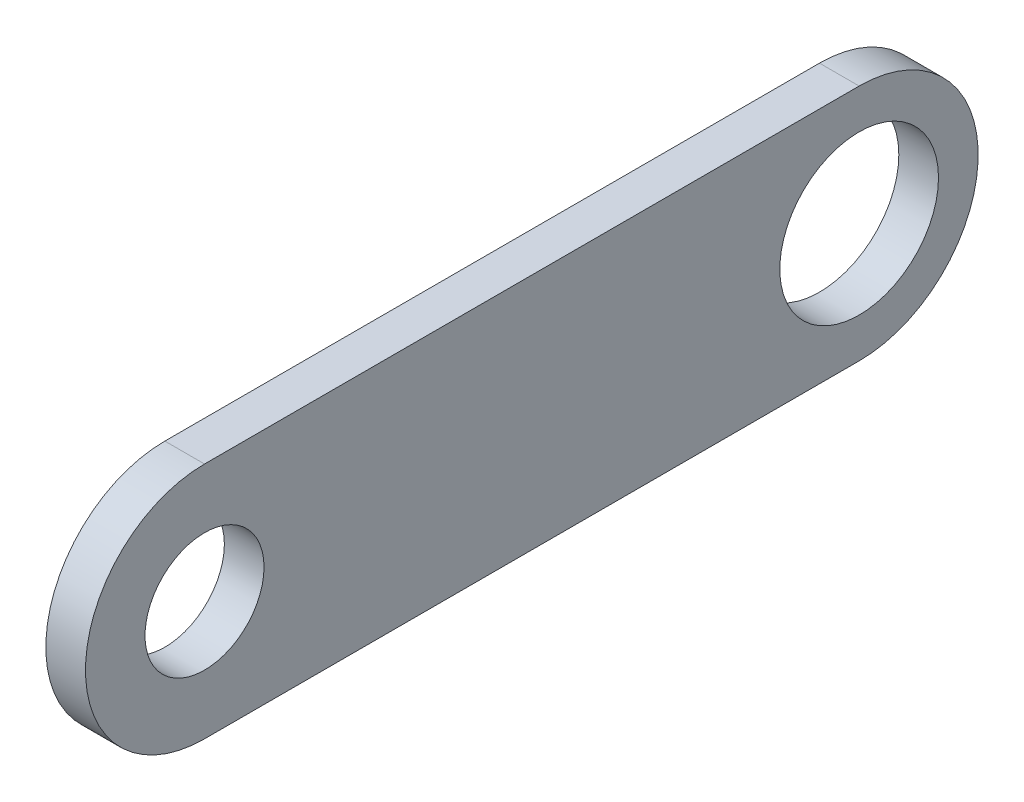
SolidWorks part; units mm, degrees
ref_plane "正面" through (0, 0, 0) normal (0, 0, 1) x (1, 0, 0)
ref_plane "平面" through (0, 0, 0) normal (0, 1, 0) x (1, 0, 0)
ref_plane "右側面" through (0, 0, 0) normal (1, 0, 0) x (0, 0, -1)
ref_plane "平面1" through (0, 0, 0) normal (-1, 0, 0) x (0, -1, 0)
sketch "ｽｹｯﾁ1" plane through (0, 0, 0) normal (-1, 0, 0) x (0, -1, 0)
  line L0 (6, -33) -> (6, 0)
  line L1 (-6, 0) -> (-6, -33)
  circle A0 centre (0, 0) radius 3
  circle A1 centre (0, -33) radius 4
  arc A2 (-6, -33) -> (6, -33) centre (0, -33) ccw
  arc A3 (6, 0) -> (-6, 0) centre (0, 0) ccw
extrude "ﾎﾞｽ - 押し出し1" add sketch "ｽｹｯﾁ1" against normal blind 2
